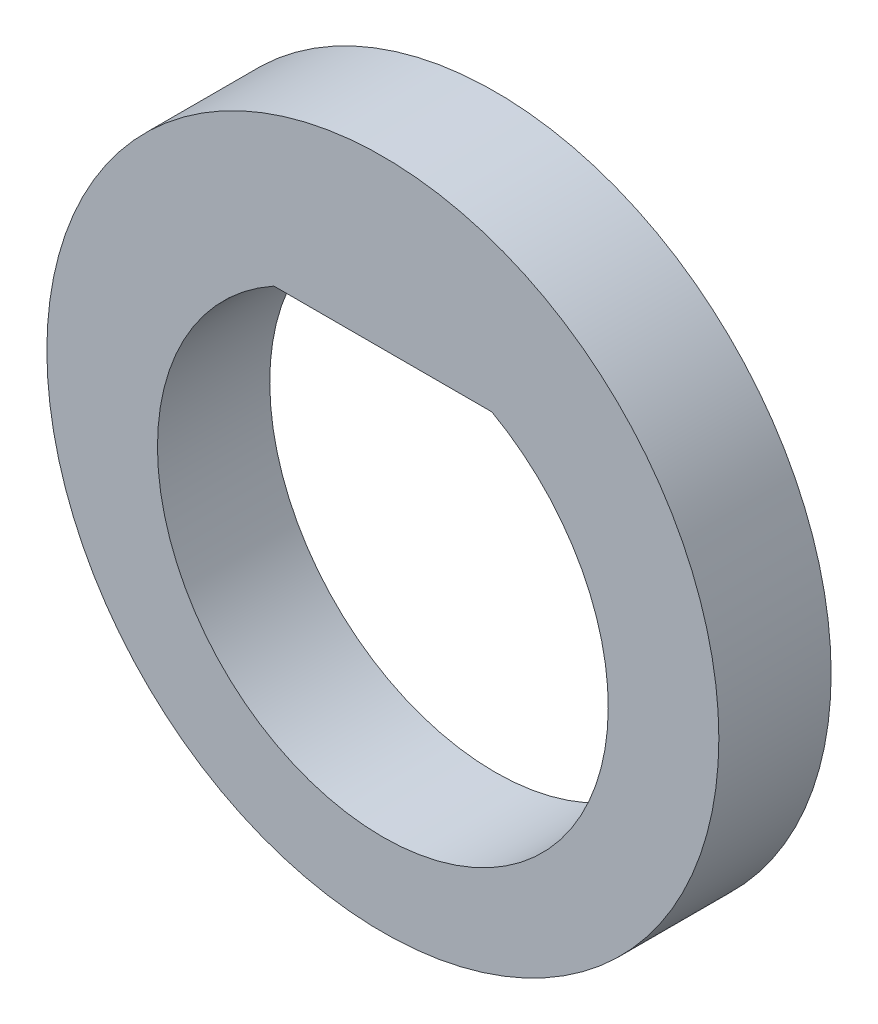
SolidWorks part; units mm, degrees
ref_plane "前视基准面" through (0, 0, 0) normal (0, 0, 1) x (1, 0, 0)
ref_plane "上视基准面" through (0, 0, 0) normal (0, 1, 0) x (1, 0, 0)
ref_plane "右视基准面" through (0, 0, 0) normal (1, 0, 0) x (0, 0, -1)
sketch "草图1" plane through (0, 0, 0) normal (0, 0, 1) x (1, 0, 0)
  line L0 (0, 0) -> (0, -0.5)
  line L1 (0, 3.515) -> (0, 3.015) construction
  line L2 (-1.9404, 3.015) -> (1.9404, 3.015)
  circle A0 centre (0, 0) radius 5.985
  circle A1 centre (0, -0.5) radius 4.015 construction
  arc A2 (-1.9404, 3.015) -> (1.9404, 3.015) centre (0, -0.5) ccw
  dimension "D1" = 0.5
  dimension "D2" = 11.97
  dimension "D3" = 8.03
  dimension "D4" = 0.5
extrude "凸台-拉伸1" add sketch "草图1" along normal blind 2 contours A0 A2 L2
